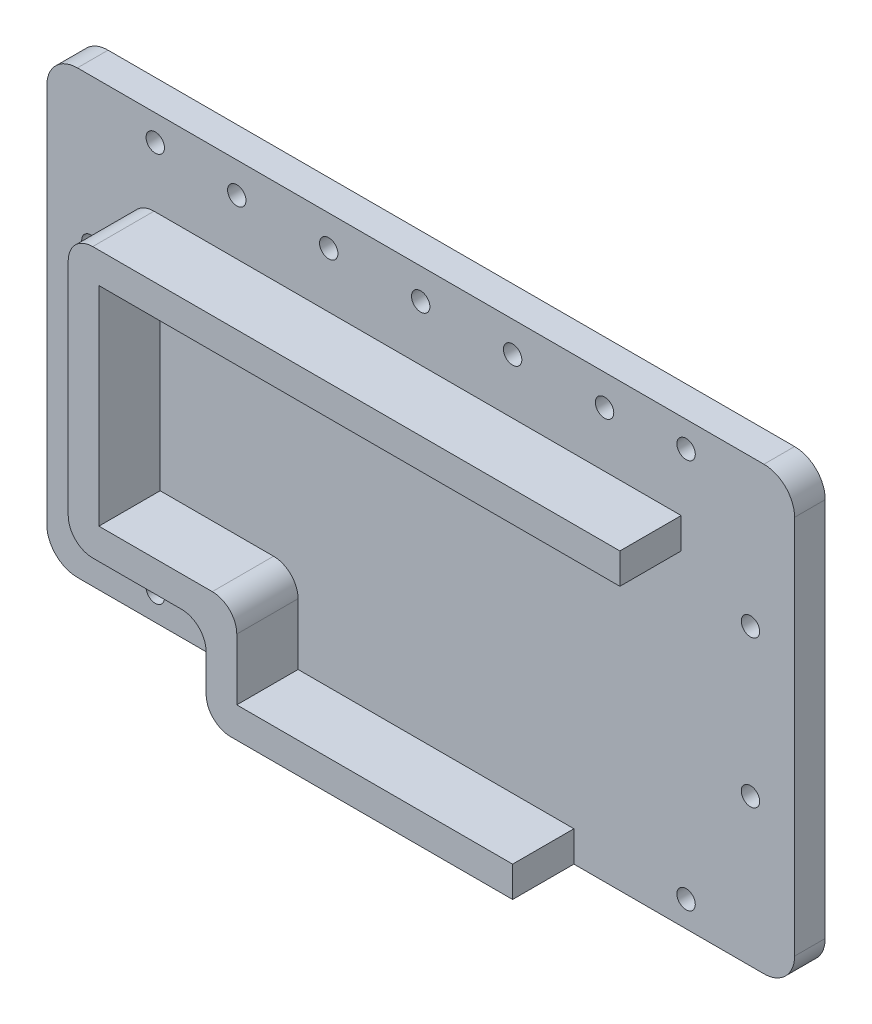
SolidWorks part; units mm, degrees
ref_plane "前视基准面" through (0, 0, 0) normal (0, 0, 1) x (1, 0, 0)
ref_plane "上视基准面" through (0, 0, 0) normal (0, 1, 0) x (1, 0, 0)
ref_plane "右视基准面" through (0, 0, 0) normal (1, 0, 0) x (0, 0, -1)
other "Configuration Table"
sketch "草图1" plane through (0, 0, 0) normal (0, 0, 1) x (1, 0, 0)
  line L1 (-61, -36) -> (61, -36)
  line L2 (-61, -36) -> (-61, 36)
  line L3 (-61, 36) -> (61, 36)
  line L4 (61, -36) -> (61, 36)
  line L5 (-61, -36) -> (61, 36) construction
  line L6 (-61, 36) -> (61, -36) construction
  point P0 (0, 0)
  dimension "D1" = 72
  dimension "D2" = 122
extrude "凸台-拉伸1" add sketch "草图1" along normal blind 5
sketch "草图4" plane through (0, 0, 5) normal (0, 0, 1) x (1, 0, 0)
  line L0 (0, 36) -> (0, -36)
  line L1 (61, 36) -> (-61, 36) construction
  line L2 (-61, -36) -> (61, -36) construction
  line L3 (-61, 0) -> (61, 0)
  line L4 (-61, 36) -> (-61, -36) construction
  line L5 (61, -36) -> (61, 36) construction
  circle A0 centre (53.8, -12) radius 1.5
  circle A1 centre (53.8, 12) radius 1.5
  circle A2 centre (-53.8, -12) radius 1.5
  circle A3 centre (-53.8, 12) radius 1.5
  dimension "D1" = 3
  dimension "D2" = 7.2
  dimension "D3" = 12
extrude "切除-拉伸2" cut sketch "草图4" against normal blind 10 contours A3 | A1 | A0 | A2
sketch "草图5" plane through (0, 0, 5) normal (0, 0, 1) x (1, 0, 0)
  line L0 (-47.5, -22) -> (47.5, -22)
  line L1 (-42.5, 17) -> (42.5, 17)
  line L2 (-42.5, 17) -> (-42.5, -17)
  line L3 (-42.5, -17) -> (42.5, -17)
  line L4 (42.5, 17) -> (42.5, -17)
  line L5 (-42.5, 17) -> (42.5, -17) construction
  line L6 (-42.5, -17) -> (42.5, 17) construction
  line L7 (47.5, 22) -> (47.5, -22)
  line L8 (-47.5, 22) -> (47.5, 22)
  line L9 (-47.5, 22) -> (-47.5, -22)
  line L10 (0, 0) -> (0, -24) construction
  line L15 (-20, -17) -> (20, -17)
  line L16 (-20, -17) -> (-20, -31)
  line L17 (-20, -31) -> (20, -31)
  line L18 (20, -17) -> (20, -31)
  line L19 (-20, -17) -> (20, -31) construction
  line L20 (-20, -31) -> (20, -17) construction
  line L21 (-25, -36) -> (25, -36)
  line L22 (25, -12) -> (25, -36)
  line L23 (-25, -12) -> (25, -12)
  line L24 (-25, -12) -> (-25, -36)
  line L25 (42.5, 17) -> (42.5, 22)
  line L26 (42.5, -17) -> (42.5, -22)
  line L27 (20, -31) -> (25, -31)
  point P1 (0, 0)
  point P10 (0, -24)
  line M23 (-61, -36) -> (61, -36)
  dimension "D1" = 85
  dimension "D2" = 34
  dimension "D4" = 40
  dimension "D5" = 14
  dimension "D3" = 5
  dimension "D6" = 5
  dimension "D7" = 5
  dimension "D8" = 5
  dimension "D9" = 5
extrude "凸台-拉伸3" add sketch "草图5" along normal blind 10 contours L1 L25 L8 L9 L0 L24 L3 L2 | L3 L24 L0 L16 | L27 L17 L16 L0 L24 L22 M23
sketch "草图6" plane through (0, 0, 5) normal (0, 0, 1) x (1, 0, 0)
  line L0 (0, 36) -> (0, -36)
  line L1 (61, 36) -> (-61, 36) construction
  line L2 (-25, -36) -> (25, -36) construction
  line L3 (0, 31) -> (15, 31) construction
  circle A0 centre (0, 31) radius 1.5
  circle A1 centre (15, 31) radius 1.5
  circle A2 centre (30, 31) radius 1.5
  circle A3 centre (-15, 31) radius 1.5
  circle A4 centre (-30, 31) radius 1.5
  dimension "D1" = 3
  dimension "D2" = 5
  dimension "D4" = 15
  dimension "D3" = 3
extrude "切除-拉伸3" cut sketch "草图6" against normal blind 15
sketch "草图7" plane through (0, 0, 5) normal (0, 0, 1) x (1, 0, 0)
  line L1 (-43.3, 31.8) -> (43.3, 31.8)
  line L2 (-43.3, 31.8) -> (-43.3, -31.8)
  line L3 (-43.3, -31.8) -> (43.3, -31.8)
  line L4 (43.3, 31.8) -> (43.3, -31.8)
  line L5 (-43.3, 31.8) -> (43.3, -31.8) construction
  line L6 (-43.3, -31.8) -> (43.3, 31.8) construction
  circle A0 centre (43.3, 31.8) radius 1.5
  circle A1 centre (43.3, -31.8) radius 1.5
  circle A2 centre (-43.3, -31.8) radius 1.5
  circle A3 centre (-43.3, 31.8) radius 1.5
  point P0 (0, 0)
  dimension "D3" = 3
  dimension "D4" = 3
  dimension "D5" = 3
  dimension "D6" = 3
  dimension "D1" = 86.6
  dimension "D2" = 63.6
extrude "切除-拉伸4" cut sketch "草图7" against normal blind 25 contours L4 A0 L1 | L1 A0 L4 | L3 A1 L4 | L4 A1 L3 | L3 A2 L2 | L1 A3 L2 | L2 A3 L1
fillet "圆角1" radius 4 5 edges at (-20, -17, 10) (-25, -36, 10) (-25, -22, 10) (-47.5, -22, 10) (-47.5, 22, 10)
fillet "圆角3" radius 5 4 edges at (-61, -36, 2.5) (-61, 36, 2.5) (61, 36, 2.5) (61, -36, 2.5)
